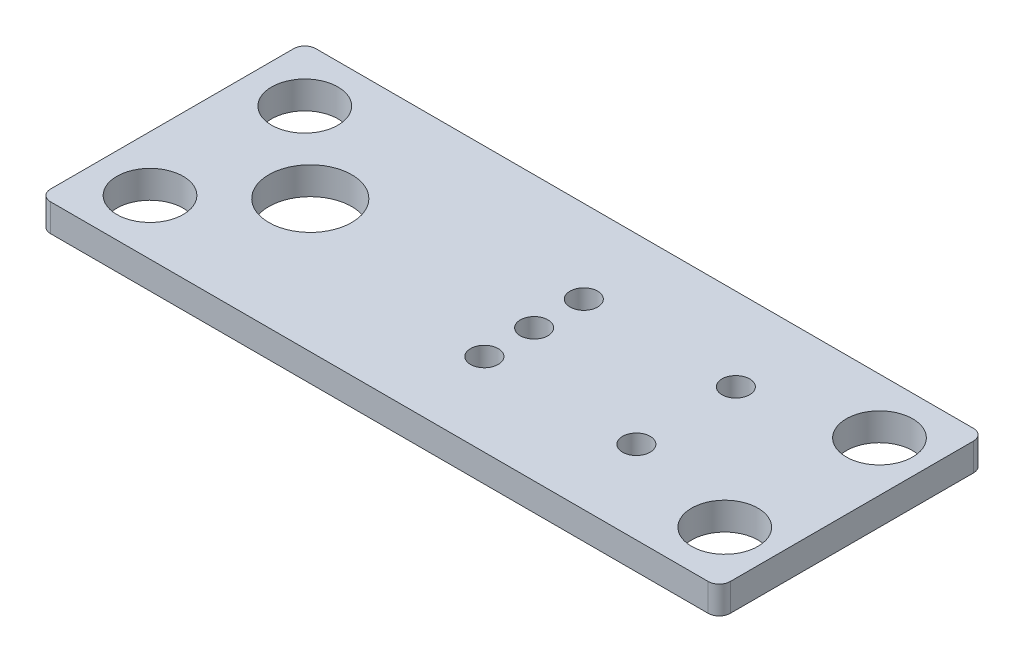
SolidWorks part; units mm, degrees
ref_plane "Front Plane" through (0, 0, 0) normal (0, 0, 1) x (1, 0, 0)
ref_plane "Top Plane" through (0, 0, 0) normal (0, 1, 0) x (1, 0, 0)
ref_plane "Right Plane" through (0, 0, 0) normal (1, 0, 0) x (0, 0, -1)
sketch "Sketch1" plane through (0, 0, 0) normal (0, 1, 0) x (1, 0, 0)
  line L0 (93, 0) -> (93, 48) construction
  line L1 (0, 0) -> (123, 0)
  line L2 (0, 0) -> (0, 48)
  line L3 (0, 48) -> (123, 48)
  line L4 (123, 0) -> (123, 48)
  circle A0 centre (10, 10) radius 6
  circle A1 centre (10, 38) radius 6
  circle A2 centre (114, 38) radius 6
  circle A3 centre (114, 10) radius 6
  circle A4 centre (25, 24) radius 7.5
  circle A6 centre (93, 15) radius 2.5
  circle A7 centre (93, 33) radius 2.5
  circle A8 centre (65.5, 15) radius 2.5
  circle A9 centre (65.5, 24) radius 2.5
  circle A10 centre (65.5, 33) radius 2.5
  point P15 (0, 24)
  point P22 (93, 24)
  dimension "D1" = 12
  dimension "D9" = 15
  dimension "D13" = 5
  dimension "D14" = 5
  dimension "D16" = 5
  dimension "D2" = 9
  dimension "D3" = 10
  dimension "D4" = 10
  dimension "D5" = 10
  dimension "D6" = 28
  dimension "D7" = 104
  dimension "D8" = 15
  dimension "D10" = 21
  dimension "D11" = 9
  dimension "D12" = 18
  dimension "D15" = 27.5
extrude "Boss-Extrude1" add sketch "Sketch1" along normal blind 5
fillet "Fillet1" radius 2 4 edges at (123, 2.5, -48) (123, 2.5, 0) (0, 2.5, 0) (0, 2.5, -48)
